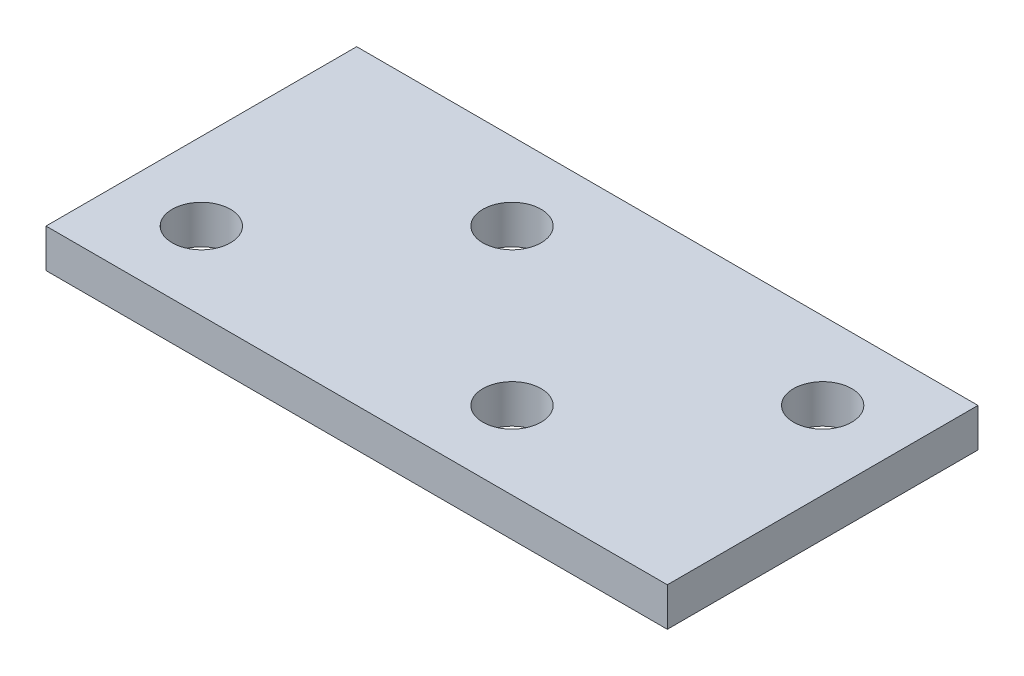
SolidWorks part; units mm, degrees
ref_plane "Alzado" through (0, 0, 0) normal (0, 0, 1) x (1, 0, 0)
ref_plane "Planta" through (0, 0, 0) normal (0, 1, 0) x (1, 0, 0)
ref_plane "Vista lateral" through (0, 0, 0) normal (1, 0, 0) x (0, 0, -1)
sketch "Croquis1" plane through (0, 0, 0) normal (0, 1, 0) x (1, 0, 0)
  line L1 (-50.8, 25.4) -> (50.8, 25.4)
  line L2 (-50.8, 25.4) -> (-50.8, -25.4)
  line L3 (-50.8, -25.4) -> (50.8, -25.4)
  line L4 (50.8, 25.4) -> (50.8, -25.4)
  line L5 (-50.8, 25.4) -> (50.8, -25.4) construction
  line L6 (-50.8, -25.4) -> (50.8, 25.4) construction
  point P0 (0, 0)
  dimension "D1" = 101.6
  dimension "D2" = 50.8
extrude "Saliente-Extruir1" add sketch "Croquis1" along normal blind 6.31
sketch "Croquis2" plane through (0, 6.31, 0) normal (0, 1, 0) x (1, 0, 0)
  line L0 (-50.8, 0) -> (50.8, 0) construction
  line L1 (-50.8, 25.4) -> (-50.8, -25.4) construction
  line L2 (50.8, -25.4) -> (50.8, 25.4) construction
  line L3 (50.8, 0) -> (0, 0) construction
  line L4 (0, 0) -> (25.4, 0) construction
  line L5 (25.4, 0) -> (25.4, 7.5763) construction
  line L6 (0, 0) -> (-50.8, 0) construction
  line L7 (-50.8, 0) -> (-25.4, 0) construction
  line L8 (-25.4, 0) -> (-25.4, 7.5763) construction
  line L9 (-25.4, 7.5763) -> (-18.1136, 12.9756) construction
  line L10 (-25.4, 0) -> (-50.8, -25.4) construction
  line L11 (-50.8, -25.4) -> (-25.4, 0) construction
  line L12 (0, 0) -> (0, 25.4) construction
  line L13 (50.8, 25.4) -> (-50.8, 25.4) construction
  line L14 (-25.4, 0) -> (-38.1, -12.7) construction
  line L15 (-38.1, -12.7) -> (-27.7316, -12.7) construction
  line L16 (-25.4, 0) -> (0, 25.4) construction
  line L17 (0, 25.4) -> (-12.7, 12.7) construction
  line L18 (-12.7, 12.7) -> (-7.8781, 12.7) construction
  circle A0 centre (-38.1, -12.7) radius 4.7625
  circle A1 centre (-12.7, 12.7) radius 4.7625
  dimension "D2" = 9.525
  dimension "D3" = 9.525
  dimension "D1" = 45
extrude "Cortar-Extruir1" cut sketch "Croquis2" against normal blind 6.31
pattern_linear "MatrizL1" count 2 spacing 50.8 along (1, 0, 0) of "Cortar-Extruir1"
